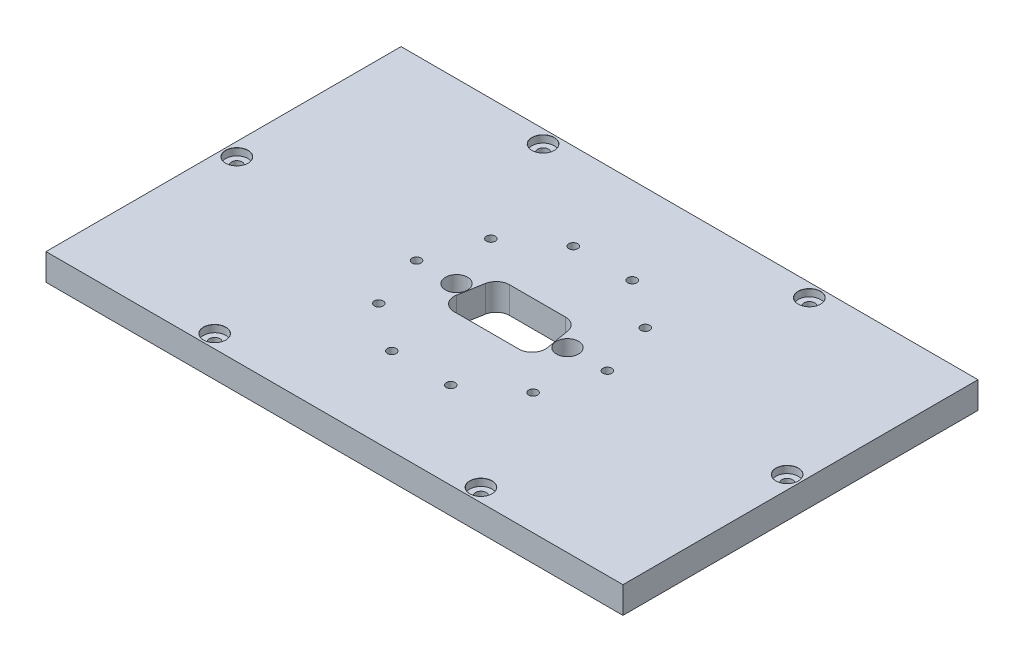
SolidWorks part; units mm, degrees
ref_plane "Ebene vorne" through (0, 0, 0) normal (0, 0, 1) x (1, 0, 0)
ref_plane "Ebene oben" through (0, 0, 0) normal (0, 1, 0) x (1, 0, 0)
ref_plane "Ebene rechts" through (0, 0, 0) normal (1, 0, 0) x (0, 0, -1)
sketch "Skizze1" plane through (0, 0, 0) normal (0, 1, 0) x (1, 0, 0)
  line L1 (0, 0) -> (130, 0)
  line L2 (0, 0) -> (0, 80)
  line L3 (0, 80) -> (130, 80)
  line L4 (130, 0) -> (130, 80)
  dimension "D1" = 80
  dimension "D2" = 130
extrude "Aufsatz-Linear austragen1" add sketch "Skizze1" along normal blind 6
hole_wizard "Ø2.4 (2.4) Durchmesser Bohrung1" positions "Skizze2" profile "Skizze3" hole size "Ø2.4" standard "DIN"
sketch "Skizze2" plane through (0, 6, 0) normal (0, 1, 0) x (1, 0, 0)
  line L0 (130, 80) -> (0, 80) construction
  line L1 (130, 0) -> (130, 80) construction
  line L2 (0, -3.3) -> (0, 3.3) construction
  line L3 (-3.3, 0) -> (3.3, 0) construction
  point P0 (35, 77)
  point P2 (95, 77)
  point P4 (127, 40)
  point P6 (95, 3)
  point P8 (35, 3)
  point P10 (3, 40)
  point P21 (133.0887, 32.8034)
  dimension "D1" = 3
  dimension "D2" = 3
  dimension "D3" = 3
  dimension "D4" = 3
  dimension "D5" = 3
  dimension "D6" = 3
  dimension "D7" = 35
  dimension "D8" = 35
  dimension "D9" = 35
  dimension "D10" = 35
  dimension "D11" = 40
  dimension "D12" = 40
sketch "Skizze3" plane through (35, 6, -77) normal (1, 0, 0) x (0, 0, 1)
  line L0 (0, 0) -> (0, 10.721)
  line L1 (0, 10.721) -> (1.2, 10)
  line L2 (1.2, 10) -> (1.2, 0.025)
  line L3 (1.2, 0.025) -> (1.225, 0)
  line L5 (1.225, 0) -> (0, 0)
  line L6 (-1.2, 0.025) -> (-1.225, 0) construction
  line L10 (0, 10.721) -> (-1.2, 10) construction
  line L11 (0, -6.35) -> (0, 107.95) construction
  dimension "Bohrerdurchmesser" = 2.4
  dimension "Bohrungstiefe" = 10
  dimension "Senkdurchmesser2 (Oben)" = 2.45
  dimension "Senkwinkel2 (Oben)" = 90
  dimension "Spitzenwinkel" = 118
hole_wizard "Stirnsenkung für M2 Flachkopfschraube mit Schlitz1" positions "Skizze6" profile "Skizze7" counterbore size "M2" standard "DIN"
sketch "Skizze6" plane through (0, 6, 0) normal (0, 1, 0) x (1, 0, 0)
  point P0 (95, 3)
  point P3 (127, 40)
  point P6 (95, 77)
  point P9 (35, 77)
  point P12 (3, 40)
  point P15 (35, 3)
sketch "Skizze7" plane through (95, 6, -3) normal (1, 0, 0) x (0, 0, 1)
  line L0 (0, 0) -> (0, 2.721)
  line L1 (0, 2.721) -> (1.2, 2)
  line L2 (1.2, 2) -> (1.2, 1.6)
  line L3 (1.2, 1.6) -> (2.5, 1.6)
  line L5 (2.5, 1.6) -> (2.5, 0.025)
  line L6 (2.5, 0.025) -> (2.525, 0)
  line L7 (2.525, 0) -> (0, 0)
  line L8 (-2.5, 0.025) -> (-2.525, 0) construction
  line L10 (0, 2.721) -> (-1.2, 2) construction
  line L11 (0, -6.35) -> (0, 107.95) construction
  dimension "Bohrerdurchmesser" = 2.4
  dimension "Bohrungstiefe" = 2
  dimension "Senkdurchmesser2" = 5
  dimension "Senktiefe2" = 1.6
  dimension "Senkdurchmesser4 (Oben)" = 5.05
  dimension "Senkwinkel2 (Oben)" = 90
  dimension "Spitzenwinkel" = 118
sketch "Skizze8" plane through (0, 6, 0) normal (0, 1, 0) x (1, 0, 0)
  line L0 (65, -24.4296) -> (65, 94.5281) construction
  line L1 (130, 0) -> (130, 80) construction
  line L2 (72.2956, 34.25) -> (57.7044, 34.25)
  line L3 (0, 80) -> (0, 0) construction
  line L4 (147.1504, 40) -> (-23.042, 40) construction
  line L5 (0, 0) -> (130, 0) construction
  line L6 (130, 80) -> (0, 80) construction
  line L7 (54.75, 37.7709) -> (55.7198, 43.2709)
  line L8 (58.6742, 45.75) -> (71.3258, 45.75)
  line L9 (74.2802, 43.2709) -> (75.25, 37.7709)
  circle A1 centre (47.6061, 52.6374) radius 1
  circle A2 centre (58.3561, 60.4477) radius 1
  circle A3 centre (71.6439, 60.4477) radius 1
  circle A4 centre (82.3939, 52.6374) radius 1
  circle A5 centre (86.5, 40) radius 1
  circle A6 centre (82.3939, 27.3626) radius 1
  circle A7 centre (71.6439, 19.5523) radius 1
  circle A8 centre (58.3561, 19.5523) radius 1
  circle A9 centre (47.6061, 27.3626) radius 1
  circle A10 centre (43.5, 40) radius 1
  arc A11 (57.7044, 34.25) -> (54.75, 37.7709) centre (57.7044, 37.25) cw
  arc A12 (55.7198, 43.2709) -> (58.6742, 45.75) centre (58.6742, 42.75) cw
  arc A13 (71.3258, 45.75) -> (74.2802, 43.2709) centre (71.3258, 42.75) cw
  arc A14 (75.25, 37.7709) -> (72.2956, 34.25) centre (72.2956, 37.25) cw
  circle A15 centre (77.5, 40) radius 2.5
  circle A16 centre (52.5, 40) radius 2.5
  point P14 (65, 40)
  dimension "D1" = 2
  dimension "D3" = 43
  dimension "D4" = 3
  dimension "D6" = 11.5
  dimension "D7" = 3
  dimension "D9" = 25
  dimension "D10" = 5
  dimension "D5" = 20.5
  dimension "D8" = 80
  dimension "D2" = 10
extrude "Schnitt-Linear austragen1" cut sketch "Skizze8" against normal up to surface (6 mm away) up to face at (35, 0, -78.2)
